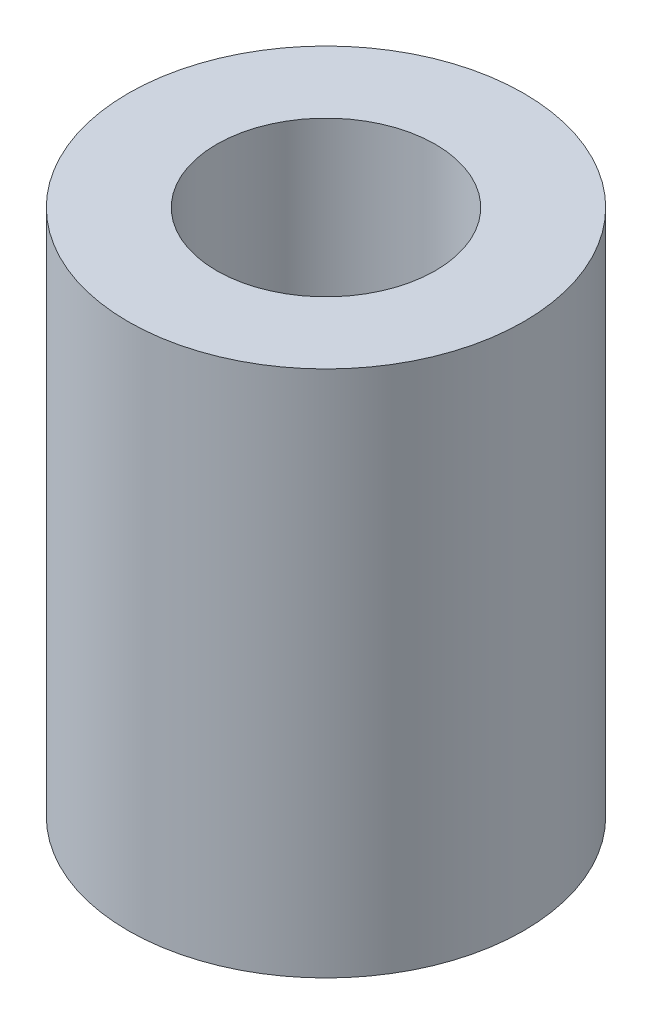
SolidWorks part; units mm, degrees
ref_plane "前视基准面" through (0, 0, 0) normal (0, 0, 1) x (1, 0, 0)
ref_plane "上视基准面" through (0, 0, 0) normal (0, 1, 0) x (1, 0, 0)
ref_plane "右视基准面" through (0, 0, 0) normal (1, 0, 0) x (0, 0, -1)
other "Configuration Table"
sketch "草图1" plane through (0, 0, 0) normal (0, 1, 0) x (1, 0, 0)
  circle A0 centre (0, 0) radius 7.5
  circle A1 centre (0, 0) radius 4.15
  dimension "D1" = 8.3
  dimension "D2" = 15
extrude "凸台-拉伸1" add sketch "草图1" along normal blind 20
